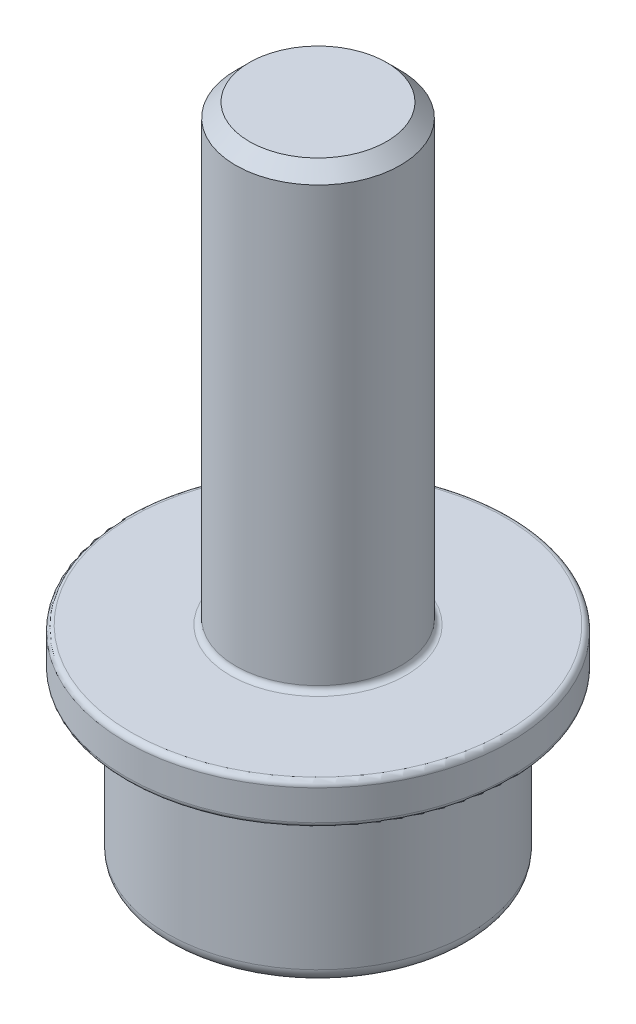
SolidWorks part; units mm, degrees
ref_plane "Front Plane" through (0, 0, 0) normal (0, 0, 1) x (1, 0, 0)
ref_plane "Top Plane" through (0, 0, 0) normal (0, 1, 0) x (1, 0, 0)
ref_plane "Right Plane" through (0, 0, 0) normal (1, 0, 0) x (0, 0, -1)
sketch "Sketch1" plane through (0, 0, 0) normal (0, 1, 0) x (1, 0, 0)
  circle A0 centre (0, 0) radius 2.75
  dimension "D1" = 5.5
extrude "Boss-Extrude1" add sketch "Sketch1" along normal blind 3
sketch "Sketch2" plane through (0, 3, 0) normal (0, 1, 0) x (1, 0, 0)
  circle A0 centre (0, 0) radius 1.5
  dimension "D1" = 3
extrude "Boss-Extrude2" add sketch "Sketch2" along normal blind 9 contours A0
sketch "Sketch3" plane through (0, 0, 0) normal (0, -1, 0) x (1, 0, 0)
  line L1 (0.9342, 0.9746) -> (-0.3769, 1.2963)
  line L2 (-0.3769, 1.2963) -> (-1.3111, 0.3217)
  line L3 (-1.3111, 0.3217) -> (-0.9342, -0.9746)
  line L4 (-0.9342, -0.9746) -> (0.3769, -1.2963)
  line L5 (0.3769, -1.2963) -> (1.3111, -0.3217)
  line L6 (1.3111, -0.3217) -> (0.9342, 0.9746)
  circle A0 centre (0, 0) radius 1.1691 construction
  dimension "D1" = 2.7
extrude "Cut-Extrude1" cut sketch "Sketch3" against normal blind 1.5
chamfer "Chamfer1" distance 0.25 distance2 0.25 6 edges at (-0.2786, 0, -1.1355) (-1.1226, 0, -0.3264) (-0.844, 0, 0.809) (0.2786, 0, 1.1355) (1.1226, 0, 0.3264) (0.844, 0, -0.809)
fillet "Fillet1" radius 0.25 1 edges at (0, 0, 2.75)
chamfer "Chamfer2" distance 0.25 angle 45 1 edges at (0, 12, 1.5)
fillet "Fillet2" radius 0.1 1 edges at (0, 3, 2.75)
sketch "Sketch4" plane through (0, 3, 0) normal (0, 1, 0) x (1, 0, 0)
  circle A0 centre (0, 0) radius 1.5
  circle A1 centre (0, 0) radius 3.5
  circle A2 centre (0, 0) radius 1.5 construction
  dimension "D1" = 7
extrude "Boss-Extrude3" add sketch "Sketch4" along normal blind 0.75
fillet "Fillet3" radius 0.1 3 edges at (0, 3.75, 1.5) (0, 3.75, 3.5) (0, 3, 3.5)
